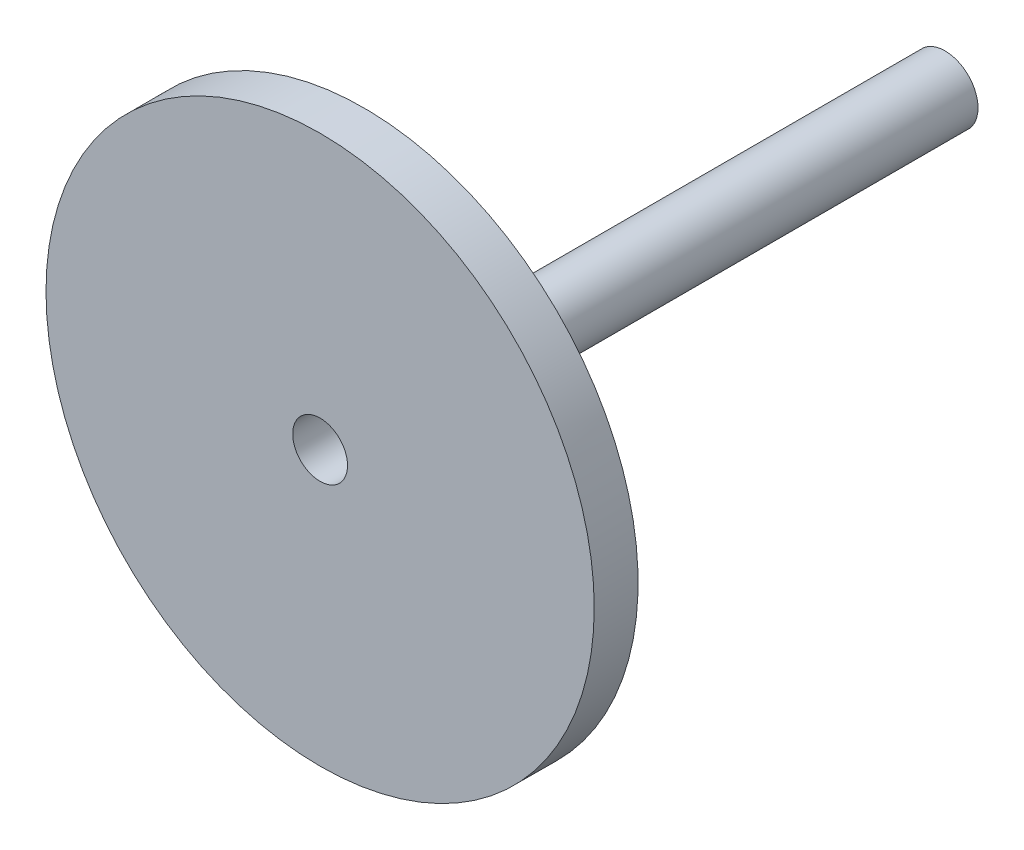
SolidWorks part; units mm, degrees
ref_plane "정면" through (0, 0, 0) normal (0, 0, 1) x (1, 0, 0)
ref_plane "윗면" through (0, 0, 0) normal (0, 1, 0) x (1, 0, 0)
ref_plane "우측면" through (0, 0, 0) normal (1, 0, 0) x (0, 0, -1)
sketch "스케치1" plane through (0, 0, 0) normal (0, 0, 1) x (1, 0, 0)
  circle A0 centre (0, 0) radius 2.5
  dimension "D1" = 5
extrude "보스-돌출1" add sketch "스케치1" along normal blind 0.2
sketch "스케치3" plane through (0, 0, 0) normal (0, 0, -1) x (-1, 0, 0)
  circle A0 centre (0, 0) radius 2.4
  circle A1 centre (0, 0) radius 2.5 construction
  circle A2 centre (0, 0) radius 2.5
  dimension "D1" = 4.8
extrude "보스-돌출2" add sketch "스케치3" along normal blind 0.2
sketch "스케치4" plane through (0, 0, 0) normal (0, 0, -1) x (-1, 0, 0)
  circle A0 centre (0, 0) radius 1.75
  circle A1 centre (0, 0) radius 1.65
  dimension "D1" = 3.5
  dimension "D2" = 3.3
extrude "컷-돌출1" cut sketch "스케치4" against normal blind 0.1
sketch "스케치5" plane through (0, 0, 0) normal (0, 0, -1) x (-1, 0, 0)
  circle A0 centre (0, 0) radius 0.3
  circle A1 centre (0, 0) radius 0.25
  dimension "D1" = 0.6
  dimension "D2" = 0.5
extrude "보스-돌출3" add sketch "스케치5" along normal blind 5.5
sketch "스케치6" plane through (0, 0, 0) normal (0, 0, -1) x (-1, 0, 0)
  circle A0 centre (0, 0) radius 0.5
  dimension "D1" = 1
sketch "스케치7" plane through (0, 0, 0) normal (0, 1, 0) x (1, 0, 0)
  line L0 (0.3, 0) -> (0.3, 0.6)
  line L2 (0.3, 0) -> (0.5, 0)
  line L4 (0.3, 0.6) -> (0.365, 0.6)
  line L5 (0.365, 0.6) -> (0.5, 0)
  line L6 (0, 0) -> (0, 1.6091) construction
  dimension "D1" = 0.6
  dimension "D2" = 0.2
  dimension "D3" = 0.065
revolve "회전1" add sketch "스케치7" angle 360 about L6
fillet "필렛1" radius 0.03 1 edges at (0.365, 0, -0.6)
sketch "스케치11" plane through (0, 0, 0) normal (0, 0, -1) x (-1, 0, 0)
  circle A1 centre (0, 0) radius 0.25
  circle A2 centre (0, 0) radius 0.25
  dimension "D1" = 0
extrude "컷-돌출3" cut sketch "스케치11" against normal blind 5.5
